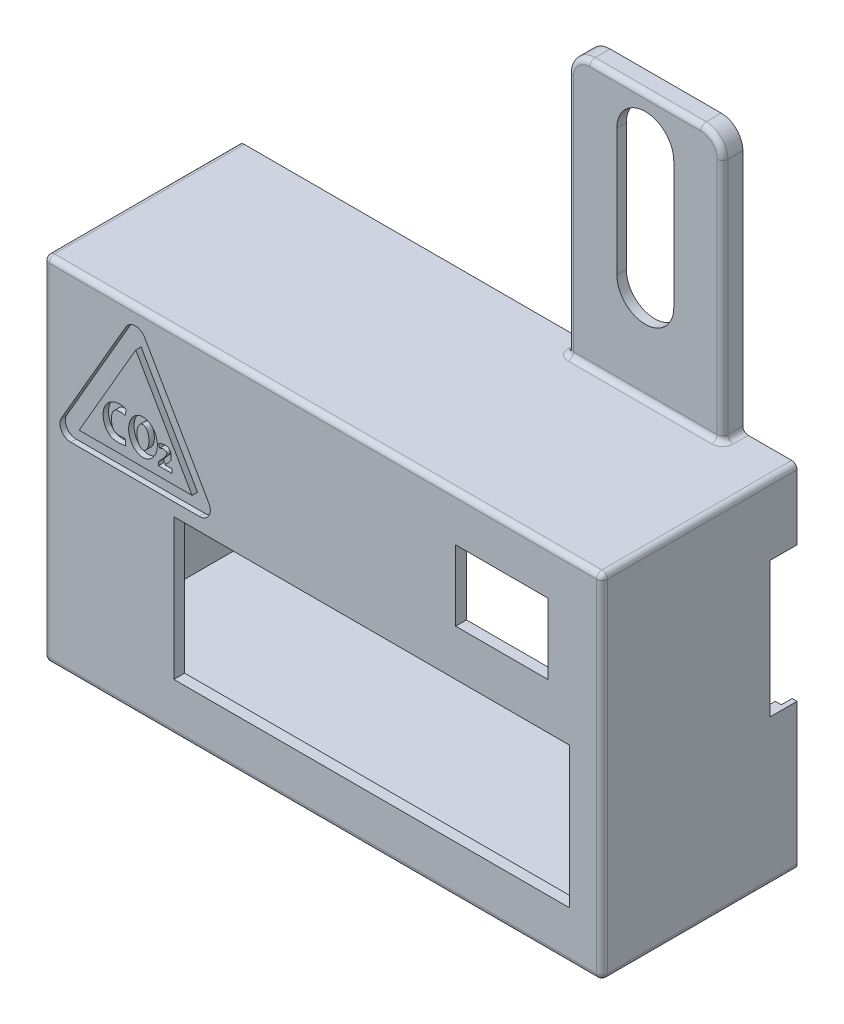
SolidWorks part; units mm, degrees
ref_plane "Front Plane" through (0, 0, 0) normal (0, 0, 1) x (1, 0, 0)
ref_plane "Top Plane" through (0, 0, 0) normal (0, 1, 0) x (1, 0, 0)
ref_plane "Right Plane" through (0, 0, 0) normal (1, 0, 0) x (0, 0, -1)
sketch "Croquis1" plane through (0, 0, 0) normal (0, 0, 1) x (1, 0, 0)
  line L1 (-51.5, 30.5) -> (51.5, 30.5)
  line L6 (-51.5, -34.5) -> (51.5, -34.5)
  line L9 (-51.5, 30.5) -> (-51.5, -34.5)
  line L10 (51.5, 30.5) -> (51.5, -34.5)
  point P1 (0, 0)
  dimension "D2" = 65
  dimension "D1" = 103
  dimension "D4" = 30.5
  dimension "D5" = 51.5
extrude "Saliente-Extruir2" add sketch "Croquis1" along normal blind 36
shell "Vaciado7" thickness 2
sketch "Croquis12" plane through (0, 0, 36) normal (0, 0, 1) x (1, 0, 0)
  line L1 (-27.5, 0.5) -> (45.5, 0.5)
  line L2 (-27.5, 0.5) -> (-27.5, -25.5)
  line L3 (-27.5, -25.5) -> (45.5, -25.5)
  line L4 (45.5, 0.5) -> (45.5, -25.5)
  line L5 (-27.5, 0.5) -> (45.5, -25.5) construction
  line L6 (-27.5, -25.5) -> (45.5, 0.5) construction
  line L7 (-51.5, -34.5) -> (51.5, -34.5) construction
  line L8 (51.5, -34.5) -> (51.5, 30.5) construction
  point P0 (9, -12.5)
  dimension "D1" = 9
  dimension "D2" = 73
  dimension "D3" = 26
  dimension "D4" = 6
extrude "Cortar-Extruir28" cut sketch "Croquis12" against normal up to next
sketch "Croquis29" plane through (0, 0, 0) normal (0, 0, -1) x (-1, 0, 0)
  line L9 (-13, 75.5) -> (-13, 30.5)
  line L10 (-17, 79.5) -> (-37.5, 79.5)
  line L12 (-51.5, 30.5) -> (51.5, 30.5) construction
  line L13 (-41.5, 30.5) -> (-13, 30.5)
  line L14 (-27.25, 71.25) -> (-27.25, 47.75) construction
  line L15 (-22, 71.25) -> (-22, 47.75)
  line L16 (-32.5, 71.25) -> (-32.5, 47.75)
  line L17 (-41.5, 30.5) -> (-41.5, 75.5)
  line L19 (-51.5, -34.5) -> (-51.5, 30.5) construction
  arc A8 (-22, 71.25) -> (-32.5, 71.25) centre (-27.25, 71.25) ccw
  arc A9 (-32.5, 47.75) -> (-22, 47.75) centre (-27.25, 47.75) ccw
  arc A10 (-41.5, 75.5) -> (-37.5, 79.5) centre (-37.5, 75.5) cw
  arc A11 (-13, 75.5) -> (-17, 79.5) centre (-17, 75.5) ccw
  point P2 (-27.25, 59.5)
  dimension "D3" = 10
  dimension "D4" = 4
  dimension "D7" = 5.25
  dimension "D2" = 4
  dimension "D1" = 28.5
  dimension "D5" = 49
  dimension "D6" = 23.5
  dimension "D8" = 14.25
  dimension "D9" = 8.25
extrude "Saliente-Extruir3" add sketch "Croquis29" against normal blind 3.75
sketch "Croquis14" plane through (0, 0, 0) normal (0, 0, -1) x (-1, 0, 0)
  line L8 (50.6, -33.6) -> (50.6, 29.6)
  line L10 (50.6, -33.6) -> (50.6, 29.6)
  line L12 (50.6, 29.6) -> (-13.9, 29.6)
  line L14 (50.6, 29.6) -> (-13.9, 29.6)
  line L16 (-13.9, 29.6) -> (-13.9, 75.5)
  line L17 (-13.9, 29.6) -> (-13.9, 75.5)
  line L18 (-17, 78.6) -> (-37.5, 78.6)
  line L19 (-17, 78.6) -> (-37.5, 78.6)
  line L20 (-40.6, 75.5) -> (-40.6, 29.6)
  line L21 (-40.6, 75.5) -> (-40.6, 29.6)
  line L22 (-40.6, 29.6) -> (-50.6, 29.6)
  line L23 (-40.6, 29.6) -> (-50.6, 29.6)
  line L28 (-50.6, 29.6) -> (-50.6, -33.6)
  line L29 (-50.6, 29.6) -> (-50.6, -33.6)
  line L30 (-50.6, -33.6) -> (50.6, -33.6)
  line L31 (-50.6, -33.6) -> (50.6, -33.6)
  arc A2 (-13.9, 75.5) -> (-17, 78.6) centre (-17, 75.5) ccw
  arc A4 (-13.9, 75.5) -> (-17, 78.6) centre (-17, 75.5) ccw
  arc A9 (-37.5, 78.6) -> (-40.6, 75.5) centre (-37.5, 75.5) ccw
  arc A10 (-37.5, 78.6) -> (-40.6, 75.5) centre (-37.5, 75.5) ccw
  dimension "D1" = 0.9
extrude "Cortar-Extruir11" cut sketch "Croquis14" against normal blind 2
sketch "Croquis16" plane through (-51.5, 0, 0) normal (-1, 0, 0) x (0, 0, 1)
  line L1 (2, -4.75) -> (12, -4.75)
  line L2 (2, -4.75) -> (2, -16.75)
  line L3 (2, -16.75) -> (12, -16.75)
  line L4 (12, -4.75) -> (12, -16.75)
  line L5 (2, -4.75) -> (12, -16.75) construction
  line L6 (2, -16.75) -> (12, -4.75) construction
  line L14 (36, -34.5) -> (0, -34.5) construction
  line L15 (0, 30.5) -> (0, -34.5) construction
  point P0 (7, -10.75)
  dimension "D1" = 2
  dimension "D2" = 23.75
  dimension "D3" = 12
  dimension "D4" = 10
extrude "Cortar-Extruir17" cut sketch "Croquis16" against normal up to next
sketch "Croquis30" plane through (0, 0, 36) normal (0, 0, 1) x (1, 0, 0)
  line L1 (24.5, 22) -> (41.5, 22)
  line L2 (24.5, 22) -> (24.5, 9)
  line L3 (24.5, 9) -> (41.5, 9)
  line L4 (41.5, 22) -> (41.5, 9)
  line L5 (51.5, -34.5) -> (51.5, 30.5) construction
  line L7 (51.5, 30.5) -> (-51.5, 30.5) construction
  dimension "D1" = 17
  dimension "D2" = 13
  dimension "D3" = 10
  dimension "D4" = 8.5
extrude "Cortar-Extruir29" cut sketch "Croquis30" against normal up to next
sketch "Croquis20" plane through (0, 0, 36) normal (0, 0, 1) x (1, 0, 0)
  line L0 (-454.7792, 225.5349) -> (-56.1125, 225.5349) construction
  line L1 (-36.28, 13.277) -> (-36.492, 12.1636)
  line L2 (-36.492, 8.5051) -> (-36.386, 7.3387)
  line L3 (-29.1222, 7.9749) -> (-27.8486, 7.9749)
  line L4 (-27.8486, 7.9749) -> (-27.8486, 7.2307)
  line L5 (-27.8486, 7.2307) -> (-30.3417, 7.2327)
  line L6 (-30.1296, 10.1488) -> (-30.3417, 10.785)
  line L7 (-34.5303, 23.616) -> (-24.1349, 5.589)
  line L8 (-24.1349, 5.589) -> (-44.9753, 5.589)
  line L9 (-44.9753, 5.589) -> (-34.5303, 23.616)
  line L13 (-32.8774, 26.4224) -> (-21.038, 5.8913)
  line L14 (-22.7706, 2.8922) -> (-46.5059, 2.8922)
  line L15 (-48.2364, 5.8949) -> (-36.3404, 26.426)
  arc A0 (-46.5059, 2.8922) -> (-48.2364, 5.8949) centre (-46.5059, 4.8922) cw
  arc A1 (-21.038, 5.8913) -> (-22.7706, 2.8922) centre (-22.7706, 4.8922) cw
  arc A2 (-32.8774, 26.4224) -> (-36.3404, 26.426) centre (-34.6099, 25.4233) ccw
  ellipse E0 centre (-33.1888, 10.3623) end of major axis (-33.2251, 7.1183) minor radius 2.6495
  ellipse E1 centre (-33.2023, 10.3643) end of major axis (-33.1775, 8.3348) minor radius 1.1049
  spline S0 degree 3 poles (-36.386, 7.3387) (-37.4557, 7.205) (-38.281, 7.1039) (-39.2491, 7.5508) (-39.2945, 7.5717) (-39.3198, 7.6215) (-39.3552, 7.6568) (-39.704, 8.0057) (-40.0063, 8.2205) (-40.2035, 8.6642) (-40.973, 10.3956) (-40.4666, 12.5403) (-38.6659, 13.277) (-37.8848, 13.5965) (-37.0556, 13.5873) (-36.28, 13.277) knots 0 0 0 0 1 1 1 2 2 2 3 3 3 4 4 4 5 5 5 5
  spline S1 degree 3 poles (-36.492, 12.1636) (-36.7218, 12.2166) (-36.9462, 12.3052) (-37.1813, 12.3226) (-37.4287, 12.341) (-37.6777, 12.3024) (-37.9236, 12.2696) (-39.2117, 12.0979) (-39.1302, 10.0085) (-38.8249, 9.1944) (-38.4713, 8.2513) (-37.2392, 8.3806) (-36.492, 8.5051) knots 0 0 0 0 1 1 1 2 2 2 3 3 3 4 4 4 4
  spline S2 degree 3 poles (-30.3417, 10.785) (-28.8974, 11.5072) (-27.7757, 11.1547) (-28.0088, 9.4065) (-28.0693, 8.9523) (-28.8656, 8.2548) (-29.1222, 7.9749) knots 0 0 0 0 1 1 1 2 2 2 2
  spline S3 degree 3 poles (-30.3417, 7.2327) (-30.324, 7.4624) (-30.3794, 7.7101) (-30.2886, 7.9219) (-30.1853, 8.1629) (-27.6056, 10.3609) (-29.4403, 10.3609) (-29.8096, 10.3609) (-29.8232, 10.2254) (-30.1296, 10.1488) knots 0 0 0 0 1 1 1 2 2 2 3 3 3 3
  dimension "D1" = 2
extrude "Cortar-Extruir24" cut sketch "Croquis20" against normal blind 1 contours L13 A2 L15 A0 L14 A1 L8 L9 L7 | S1 L1 S0 L2 | E0 E1 | S3 L5 L4 L3 S2 L6
sketch "Croquis31" plane through (51.5, 0, 0) normal (1, 0, 0) x (0, 0, -1)
  line L0 (0, -34.5) -> (0, 30.5) construction
  line L1 (0, 17.5) -> (-5, 17.5)
  line L2 (0, 17.5) -> (0, -7.5)
  line L3 (0, -7.5) -> (-5, -7.5)
  line L4 (-5, 17.5) -> (-5, -7.5)
  line L5 (-36, 30.5) -> (0, 30.5) construction
  dimension "D1" = 5
  dimension "D2" = 25
  dimension "D3" = 13
extrude "Cortar-Extruir30" cut sketch "Croquis31" against normal up to next
fillet "Redondeo1" radius 1 16 edges at (13, 30.5, 1.875) (41.5, 30.5, 1.875) (13, 53, 3.75) (14.1716, 78.3284, 3.75) (27.25, 79.5, 3.75) (40.3284, 78.3284, 3.75) (27.25, 30.5, 3.75) (41.5, 53, 3.75) (-51.5, 30.5, 18) (-51.5, -2, 36) (-51.5, -34.5, 18) (51.5, -34.5, 18) (0, -34.5, 36) (51.5, -2, 36) (51.5, 30.5, 18) (0, 30.5, 36)
